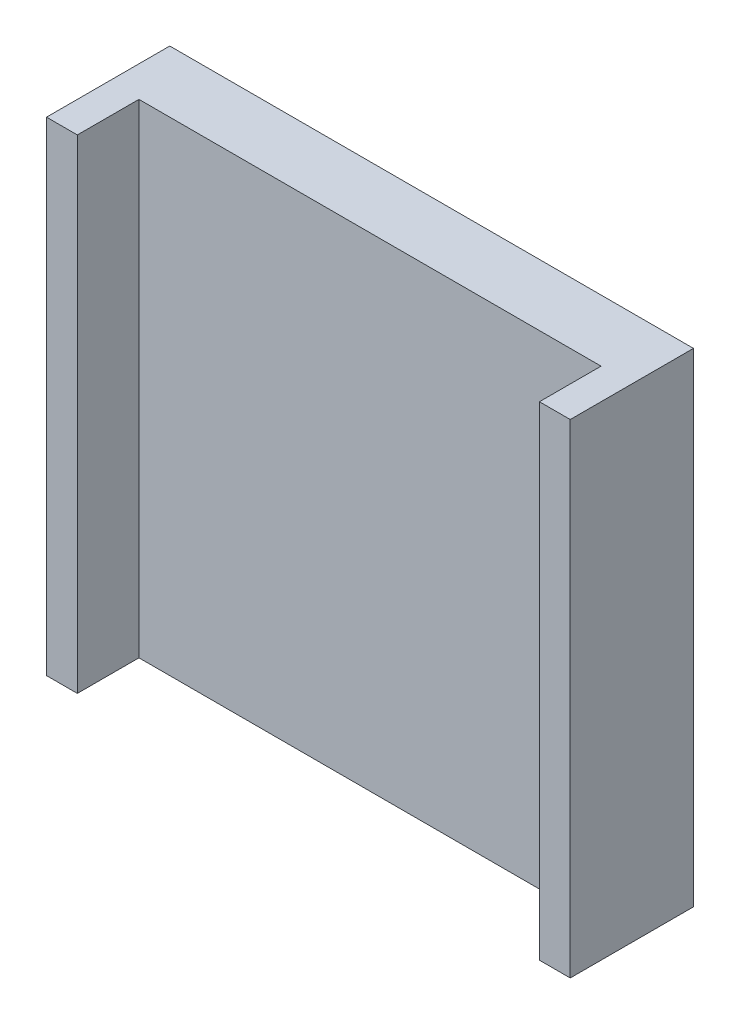
SolidWorks part; units mm, degrees
ref_plane "Front Plane" through (0, 0, 0) normal (0, 0, 1) x (1, 0, 0)
ref_plane "Top Plane" through (0, 0, 0) normal (0, 1, 0) x (1, 0, 0)
ref_plane "Right Plane" through (0, 0, 0) normal (1, 0, 0) x (0, 0, -1)
sketch "Sketch1" plane through (0, 0, 0) normal (0, 1, 0) x (1, 0, 0)
  line L1 (-30.2802, 22.2759) -> (54.7198, 22.2759)
  line L2 (-30.2802, 22.2759) -> (-30.2802, 2.2759)
  line L3 (-30.2802, 2.2759) -> (54.7198, 2.2759)
  line L4 (54.7198, 22.2759) -> (54.7198, 2.2759)
  dimension "D1" = 85
  dimension "D2" = 20
extrude "Boss-Extrude1" add sketch "Sketch1" along normal blind 78.5
sketch "Sketch2" plane through (0, 78.5, 0) normal (0, 1, 0) x (1, 0, 0)
  line L0 (-30.2802, 2.2759) -> (54.7198, 2.2759) construction
  line L1 (-25.2802, 2.2759) -> (49.7198, 2.2759)
  line L2 (-25.2802, 2.2759) -> (-25.2802, 12.2759)
  line L3 (-25.2802, 12.2759) -> (49.7198, 12.2759)
  line L4 (49.7198, 2.2759) -> (49.7198, 12.2759)
  line L5 (-30.2802, 22.2759) -> (-30.2802, 2.2759) construction
  dimension "D1" = 75
  dimension "D2" = 10
  dimension "D3" = 5
extrude "Cut-Extrude1" cut sketch "Sketch2" against normal blind 88.5
